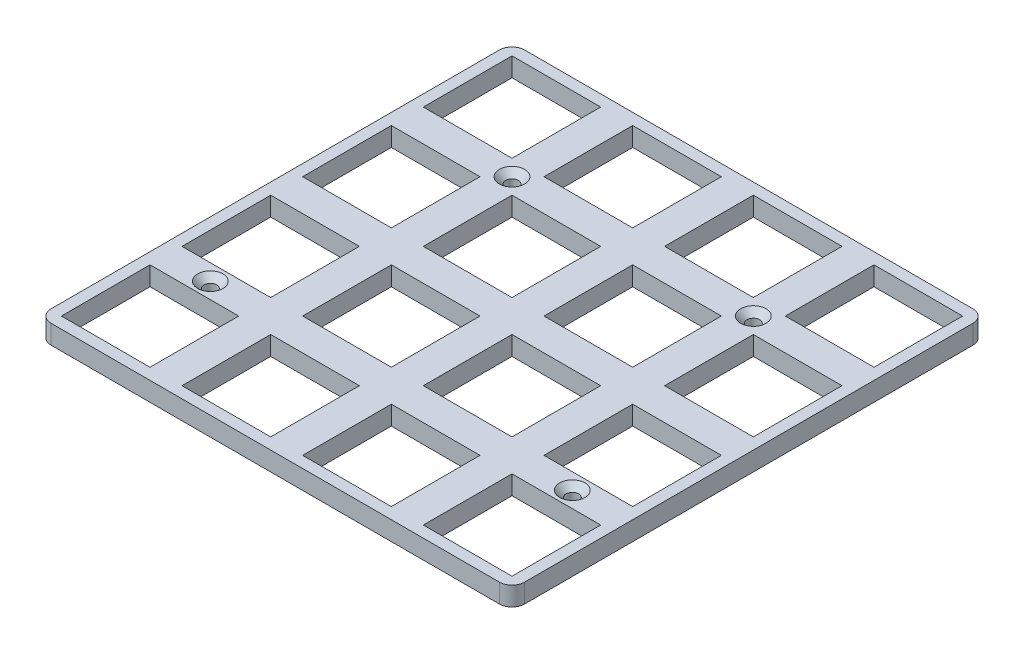
SolidWorks part; units mm, degrees
ref_plane "Front Plane" through (0, 0, 0) normal (0, 0, 1) x (1, 0, 0)
ref_plane "Top Plane" through (0, 0, 0) normal (0, 1, 0) x (1, 0, 0)
ref_plane "Right Plane" through (0, 0, 0) normal (1, 0, 0) x (0, 0, -1)
sketch "Sketch5" plane through (0, 0, 0) normal (1, 0, 0) x (0, 0, -1)
  line L0 (0, 0) -> (0, 13.4604) construction
sketch "Sketch1" plane through (0, 0, 0) normal (0, 1, 0) x (1, 0, 0)
  line L5 (-16.525, 21.575) -> (-16.525, 35.575)
  line L6 (-37.575, -37.575) -> (37.575, -37.575)
  line L11 (-37.575, -37.575) -> (-37.575, 37.575)
  line L12 (-37.575, 37.575) -> (37.575, 37.575)
  line L72 (37.575, -37.575) -> (37.575, 37.575)
  line L88 (-37.575, -37.575) -> (37.575, 37.575) construction
  line L89 (-37.575, 37.575) -> (37.575, -37.575) construction
  line L90 (-35.575, 21.575) -> (-21.575, 21.575)
  line L91 (-35.575, 21.575) -> (-35.575, 35.575)
  line L92 (-35.575, 35.575) -> (-21.575, 35.575)
  line L93 (-21.575, 21.575) -> (-21.575, 35.575)
  line L94 (-35.575, 21.575) -> (-21.575, 35.575) construction
  line L95 (-35.575, 35.575) -> (-21.575, 21.575) construction
  line L96 (-16.525, 21.575) -> (-2.525, 21.575)
  line L97 (-2.525, 21.575) -> (-2.525, 35.575)
  line L98 (-16.525, 35.575) -> (-2.525, 35.575)
  line L99 (2.525, 21.575) -> (2.525, 35.575)
  line L100 (2.525, 21.575) -> (16.525, 21.575)
  line L101 (16.525, 21.575) -> (16.525, 35.575)
  line L102 (2.525, 35.575) -> (16.525, 35.575)
  line L103 (21.575, 21.575) -> (21.575, 35.575)
  line L104 (21.575, 21.575) -> (35.575, 21.575)
  line L105 (35.575, 21.575) -> (35.575, 35.575)
  line L106 (21.575, 35.575) -> (35.575, 35.575)
  line L107 (-16.525, 2.525) -> (-16.525, 16.525)
  line L108 (-16.525, 2.525) -> (-2.525, 2.525)
  line L109 (-2.525, 2.525) -> (-2.525, 16.525)
  line L110 (-16.525, 16.525) -> (-2.525, 16.525)
  line L111 (2.525, 2.525) -> (2.525, 16.525)
  line L112 (2.525, 2.525) -> (16.525, 2.525)
  line L113 (16.525, 2.525) -> (16.525, 16.525)
  line L114 (2.525, 16.525) -> (16.525, 16.525)
  line L115 (21.575, 2.525) -> (21.575, 16.525)
  line L116 (21.575, 2.525) -> (35.575, 2.525)
  line L117 (35.575, 2.525) -> (35.575, 16.525)
  line L118 (21.575, 16.525) -> (35.575, 16.525)
  line L119 (-16.525, -16.525) -> (-16.525, -2.525)
  line L120 (-16.525, -16.525) -> (-2.525, -16.525)
  line L121 (-2.525, -16.525) -> (-2.525, -2.525)
  line L122 (-16.525, -2.525) -> (-2.525, -2.525)
  line L123 (2.525, -16.525) -> (2.525, -2.525)
  line L124 (2.525, -16.525) -> (16.525, -16.525)
  line L125 (16.525, -16.525) -> (16.525, -2.525)
  line L126 (2.525, -2.525) -> (16.525, -2.525)
  line L127 (21.575, -16.525) -> (21.575, -2.525)
  line L128 (21.575, -16.525) -> (35.575, -16.525)
  line L129 (35.575, -16.525) -> (35.575, -2.525)
  line L130 (21.575, -2.525) -> (35.575, -2.525)
  line L131 (-16.525, -35.575) -> (-16.525, -21.575)
  line L132 (-16.525, -35.575) -> (-2.525, -35.575)
  line L133 (-2.525, -35.575) -> (-2.525, -21.575)
  line L134 (-16.525, -21.575) -> (-2.525, -21.575)
  line L135 (2.525, -35.575) -> (2.525, -21.575)
  line L136 (2.525, -35.575) -> (16.525, -35.575)
  line L137 (16.525, -35.575) -> (16.525, -21.575)
  line L138 (2.525, -21.575) -> (16.525, -21.575)
  line L139 (21.575, -35.575) -> (21.575, -21.575)
  line L140 (21.575, -35.575) -> (35.575, -35.575)
  line L141 (35.575, -35.575) -> (35.575, -21.575)
  line L142 (21.575, -21.575) -> (35.575, -21.575)
  line L143 (-35.575, 2.525) -> (-35.575, 16.525)
  line L144 (-35.575, 2.525) -> (-21.575, 2.525)
  line L145 (-21.575, 2.525) -> (-21.575, 16.525)
  line L146 (-35.575, 16.525) -> (-21.575, 16.525)
  line L147 (-35.575, -16.525) -> (-35.575, -2.525)
  line L148 (-35.575, -16.525) -> (-21.575, -16.525)
  line L149 (-21.575, -16.525) -> (-21.575, -2.525)
  line L150 (-35.575, -2.525) -> (-21.575, -2.525)
  line L151 (-35.575, -35.575) -> (-35.575, -21.575)
  line L152 (-35.575, -35.575) -> (-21.575, -35.575)
  line L153 (-21.575, -35.575) -> (-21.575, -21.575)
  line L154 (-35.575, -21.575) -> (-21.575, -21.575)
  line L155 (-35.575, 21.575) -> (-16.525, 21.575) construction
  line L156 (-35.575, 21.575) -> (-35.575, 2.525) construction
  point P0 (0, 0)
  point P6 (-28.575, 28.575)
  dimension "D1" = 2
  dimension "D2" = 14
  dimension "D5" = 90
  dimension "D6" = 19.05
  dimension "D7" = 19.05
  dimension "D3" = 4
  dimension "D8" = 75.15
  dimension "D9" = 5.05
  dimension "D10" = 71.15
  dimension "D4" = 4
extrude "Boss-Extrude1" add sketch "Sketch1" along normal blind 3
sketch "Sketch2" plane through (0, 3, 0) normal (0, 1, 0) x (1, 0, 0)
  line L0 (-28.575, -16.525) -> (-28.575, -21.575) construction
  line L5 (-35.575, -16.525) -> (-21.575, -16.525) construction
  line L7 (-21.575, -21.575) -> (-35.575, -21.575) construction
  line L8 (-28.575, -19.05) -> (0, -19.05) construction
  line L9 (-21.575, 16.525) -> (-16.525, 16.525) construction
  line L10 (-21.575, 16.525) -> (-21.575, 21.575) construction
  line L11 (-21.575, 21.575) -> (-16.525, 21.575) construction
  line L12 (-16.525, 16.525) -> (-16.525, 21.575) construction
  line L15 (-21.575, 16.525) -> (-16.525, 21.575) construction
  line L20 (-21.575, 21.575) -> (-16.525, 16.525) construction
  line L22 (-19.05, 19.05) -> (0, 19.05) construction
  circle A0 centre (-19.05, 19.05) radius 1
  circle A1 centre (-28.575, -19.05) radius 1
  point P8 (-19.05, 19.05)
  point P17 (-28.575, -19.05)
  dimension "D1" = 2
  dimension "D2" = 2
  dimension "D3" = 19.05
  dimension "D4" = 28.575
extrude "Cut-Extrude1" cut sketch "Sketch2" against normal up to surface (3 mm away) up to face at (0, 0, 0)
sketch "Sketch3" plane through (0, 3, 0) normal (0, 1, 0) x (1, 0, 0)
  circle A2 centre (-19.05, 19.05) radius 2
  circle A3 centre (-19.05, 19.05) radius 2
  circle A4 centre (-28.575, -19.05) radius 2
  circle A5 centre (-28.575, -19.05) radius 2
  dimension "D1" = 1
  dimension "D2" = 1
extrude "Cut-Extrude2" [suppressed] cut sketch "Sketch3" against normal blind 1
chamfer "Chamfer1" distance 1 angle 45 2 edges at (-19.05, 3, -18.05) (-28.575, 3, 20.05)
mirror "Mirror1" about plane through (0, 0, 0) normal (1, 0, 0) of "Chamfer1", "Cut-Extrude1"
other "Move Face1" face at (37.575, 1.5, 0) face at (0, 1.5, -37.575) face at (0, 1.5, 37.575) face at (-37.575, 1.5, 0) parameters "D1"=0.2
fillet "Fillet1" radius 2 4 edges at (-37.375, 1.5, -37.375) (37.375, 1.5, -37.375) (37.375, 1.5, 37.375) (-37.375, 1.5, 37.375)
equation "\"screwhole\"=2"
equation "\"D2@Sketch2\"=\"screwhole\""
equation "\"D1@Sketch2\"=\"screwhole\""
